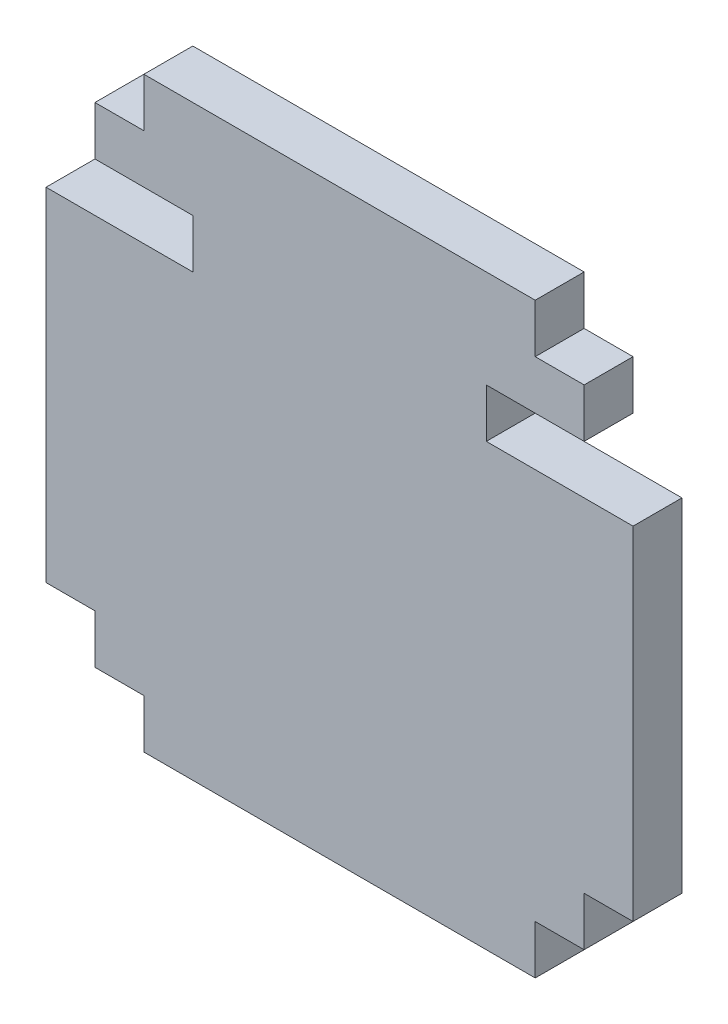
SolidWorks part; units mm, degrees
ref_plane "Front Plane" through (0, 0, 0) normal (0, 0, 1) x (1, 0, 0)
ref_plane "Top Plane" through (0, 0, 0) normal (0, 1, 0) x (1, 0, 0)
ref_plane "Right Plane" through (0, 0, 0) normal (1, 0, 0) x (0, 0, -1)
sketch "Sketch1" plane through (0, 0, 0) normal (0, 0, 1) x (1, 0, 0)
  line L0 (-25.4, -3.175) -> (25.4, -3.175)
  line L1 (25.4, -3.175) -> (25.4, 3.175)
  line L2 (25.4, 3.175) -> (31.75, 3.175)
  line L3 (31.75, 3.175) -> (31.75, 9.525)
  line L4 (31.75, 9.525) -> (38.1, 9.525)
  line L5 (38.1, 9.525) -> (38.1, 60.325)
  line L6 (38.1, 60.325) -> (31.75, 60.325)
  line L7 (31.75, 60.325) -> (31.75, 66.675)
  line L8 (31.75, 66.675) -> (25.4, 66.675)
  line L9 (25.4, 66.675) -> (25.4, 73.025)
  line L10 (25.4, 73.025) -> (-25.4, 73.025)
  line L11 (-25.4, 73.025) -> (-25.4, 66.675)
  line L12 (-25.4, 66.675) -> (-31.75, 66.675)
  line L13 (-31.75, 66.675) -> (-31.75, 60.325)
  line L14 (-31.75, 60.325) -> (-38.1, 60.325)
  line L15 (-25.4, -3.175) -> (-25.4, 3.175)
  line L16 (-25.4, 3.175) -> (-31.75, 3.175)
  line L17 (-31.75, 3.175) -> (-31.75, 9.525)
  line L18 (-31.75, 9.525) -> (-38.1, 9.525)
  line L19 (-38.1, 9.525) -> (-38.1, 60.325)
  line L20 (38.1, 3.175) -> (38.1, -3.175) construction
  line L21 (-38.1, 3.175) -> (-38.1, -3.175) construction
  dimension "D1" = 76.2
  dimension "D2" = 6.35
extrude "Boss-Extrude1" add sketch "Sketch1" along normal up to surface (6.35 mm away)
sketch "Sketch3" plane through (0, 0, 6.35) normal (0, 0, 1) x (1, 0, 0)
  line L0 (38.1, 60.325) -> (19.05, 60.325)
  line L1 (19.05, 60.325) -> (19.05, 53.975)
  line L2 (19.05, 53.975) -> (38.1, 53.975)
  line L3 (38.1, 60.325) -> (38.1, 9.525) construction
  line L4 (38.1, 53.975) -> (38.1, 60.325)
  line L5 (-19.05, 60.325) -> (-19.05, 53.975)
  line L6 (-19.05, 53.975) -> (-38.1, 53.975)
  line L7 (-38.1, 9.525) -> (-38.1, 60.325) construction
  line L8 (-38.1, 53.975) -> (-38.1, 60.325)
  line L9 (-38.1, 60.325) -> (-19.05, 60.325)
  dimension "D1" = 6.35
  dimension "D2" = 6.35
  dimension "D3" = 19.05
  dimension "D4" = 19.05
extrude "Cut-Extrude1" cut sketch "Sketch3" against normal through all
